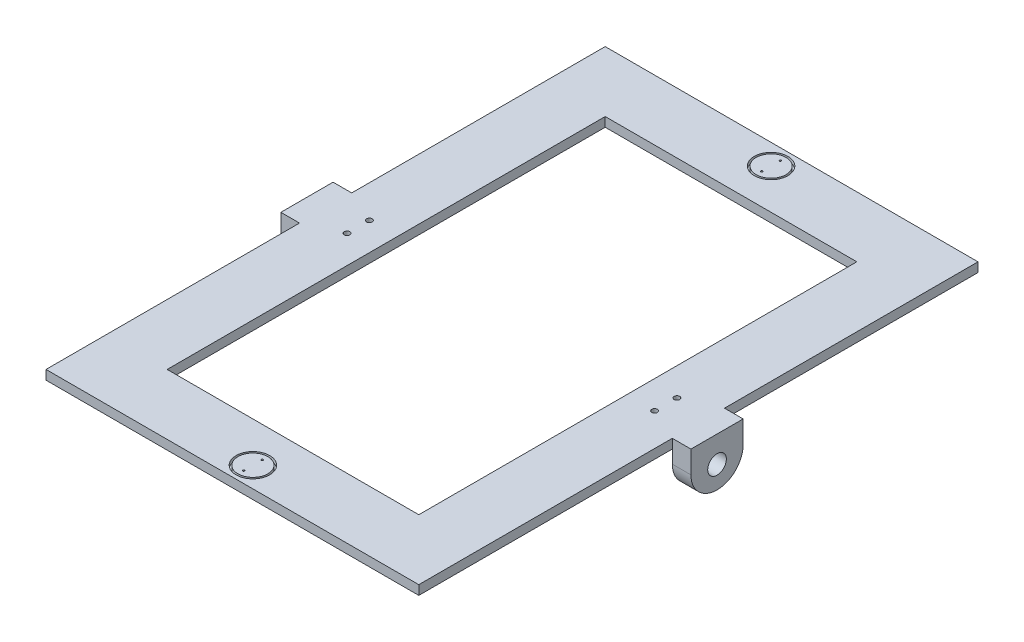
SolidWorks part; units mm, degrees
ref_plane "Front Plane" through (0, 0, 0) normal (0, 0, 1) x (1, 0, 0)
ref_plane "Top Plane" through (0, 0, 0) normal (0, 1, 0) x (1, 0, 0)
ref_plane "Right Plane" through (0, 0, 0) normal (1, 0, 0) x (0, 0, -1)
sketch "Sketch1" plane through (0, 0, 0) normal (0, 1, 0) x (1, 0, 0)
  line L1 (-100, 150) -> (100, 150)
  line L2 (-100, 150) -> (-100, -150)
  line L3 (-100, -150) -> (100, -150)
  line L4 (100, 150) -> (100, -150)
  line L5 (-100, 150) -> (100, -150) construction
  line L6 (-100, -150) -> (100, 150) construction
  line L7 (-67.5, 117.5) -> (67.5, 117.5)
  line L8 (-67.5, 117.5) -> (-67.5, -117.5)
  line L9 (-67.5, -117.5) -> (67.5, -117.5)
  line L10 (67.5, 117.5) -> (67.5, -117.5)
  line L11 (-67.5, 117.5) -> (67.5, -117.5) construction
  line L12 (-67.5, -117.5) -> (67.5, 117.5) construction
  point P0 (0, 0)
  point P6 (0, 0)
  dimension "D1" = 200
  dimension "D2" = 300
  dimension "D3" = 135
  dimension "D4" = 235
extrude "Boss-Extrude1" add sketch "Sketch1" along normal blind 5
sketch "Sketch3" plane through (100, 0, 0) normal (1, 0, 0) x (0, 0, -1)
  line L0 (-150, 5) -> (150, 5) construction
  line L1 (-14, 5) -> (14, 5)
  line L2 (-14, 5) -> (-14, -7)
  line L4 (14, 5) -> (14, -7)
  line L5 (0, 5) -> (0, -21) construction
  arc A0 (14, -7) -> (-14, -7) centre (0, -7) cw
  circle A1 centre (0, -9.1274) radius 5
  point P11 (0, 0)
  dimension "D3" = 14
  dimension "D4" = 10
  dimension "D1" = 28
  dimension "D2" = 12
extrude "Boss-Extrude2" add sketch "Sketch3" along normal blind 10
mirror "Mirror1" about plane through (0, 0, 0) normal (1, 0, 0) of "Boss-Extrude2"
sketch "Sketch4" plane through (0, 5, 0) normal (0, 1, 0) x (1, 0, 0)
  line L0 (0, 150) -> (0, -150) construction
  line L1 (100, 150) -> (-100, 150) construction
  line L2 (-100, -150) -> (100, -150) construction
  circle A0 centre (0, -139) radius 9
  circle A1 centre (0, -139) radius 8
  point P11 (-44.172, -128.7177)
  dimension "D1" = 18
  dimension "D2" = 16
  dimension "D3" = 11
extrude "Cut-Extrude1" cut sketch "Sketch4" against normal blind 2
mirror "Mirror2" about plane through (0, 0, 0) normal (0, 0, 1) of "Cut-Extrude1"
sketch "Sketch5" plane through (0, 5, 0) normal (0, 1, 0) x (1, 0, 0)
  line L0 (0, -130) -> (0, -148) construction
  line L1 (-9, -139) -> (9, -139) construction
  circle A0 centre (0, -139) radius 9 construction
  circle A1 centre (0, -139) radius 9 construction
  circle A2 centre (0, -134) radius 0.5
  circle A3 centre (0, -144) radius 0.5
  point P13 (0, -139)
  dimension "D1" = 1
  dimension "D2" = 1
  dimension "D3" = 10
  dimension "D4" = 5
extrude "Cut-Extrude2" cut sketch "Sketch5" against normal up to surface (5 mm away) up to face at (0, 0, 0)
mirror "Mirror3" about plane through (0, 0, 0) normal (0, 0, 1) of "Cut-Extrude2"
sketch "Sketch6" plane through (0, 5, 0) normal (0, 1, 0) x (1, 0, 0)
  line L0 (-110, 0) -> (110, 0) construction
  line L1 (-110, 14) -> (-110, -14) construction
  line L2 (110, 14) -> (110, -14) construction
  circle A0 centre (-82.5, 6) radius 1.5
  circle A1 centre (-82.5, -6) radius 1.5
  point P8 (-85.9765, 0)
  point P10 (0, 0)
  point P11 (0, 0)
  point P12 (0, 0)
  point P13 (0, 0)
  point P14 (0, 0)
  dimension "D1" = 3
  dimension "D2" = 12
extrude "Cut-Extrude3" cut sketch "Sketch6" against normal up to surface (5 mm away) up to face at (0, 0, -133.5)
mirror "Mirror4" about plane through (0, 0, 0) normal (1, 0, 0) of "Cut-Extrude3"
